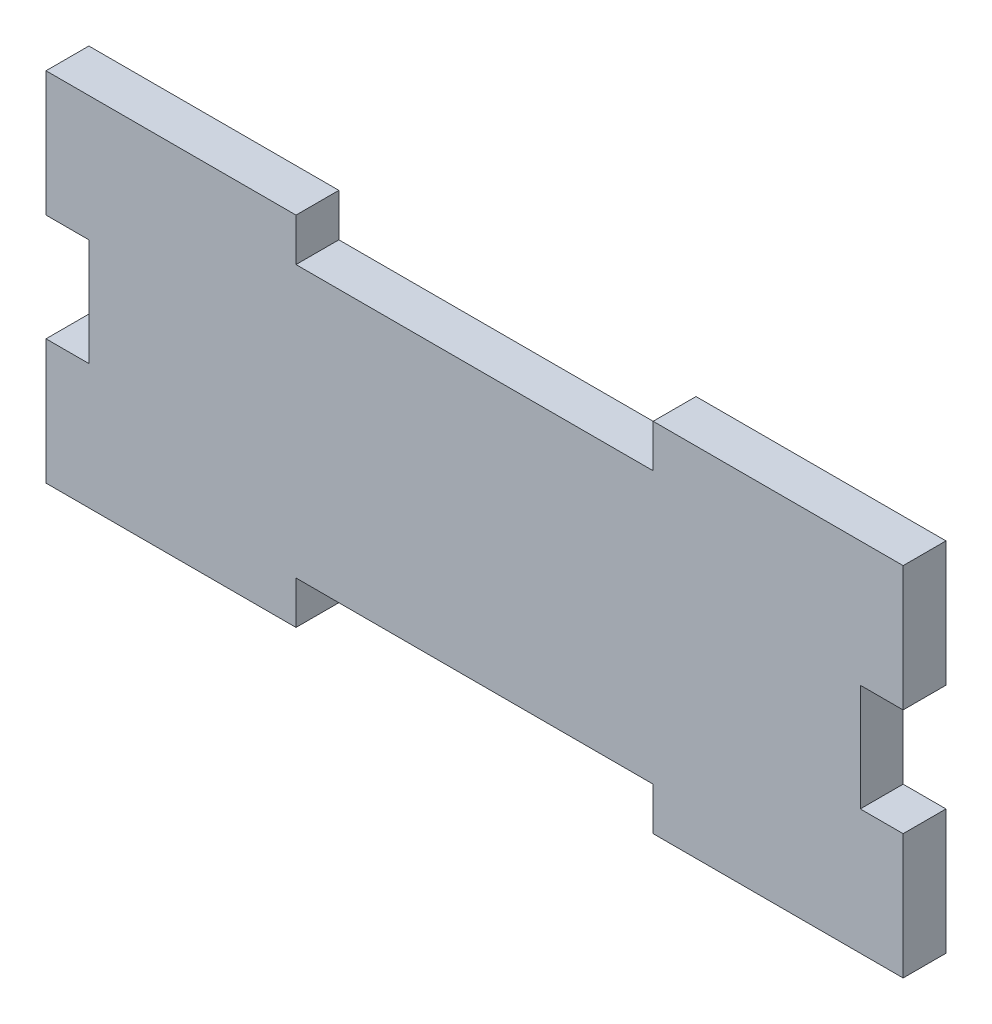
SolidWorks part; units mm, degrees
material "6061-T6 (SS)"
ref_plane "Alzado" through (0, 0, 0) normal (0, 0, 1) x (1, 0, 0)
ref_plane "Planta" through (0, 0, 0) normal (0, 1, 0) x (1, 0, 0)
ref_plane "Vista lateral" through (0, 0, 0) normal (1, 0, 0) x (0, 0, -1)
sketch "Croquis1" plane through (0, 0, 0) normal (0, 0, 1) x (1, 0, 0)
  line L0 (-25, 19) -> (-25, 25)
  line L1 (-25, -19) -> (25, -19)
  line L2 (-60, -25) -> (-60, -7.5)
  line L3 (-25, 19) -> (25, 19)
  line L4 (60, -25) -> (60, -7.5)
  line L5 (25, 25) -> (60, 25)
  line L6 (25, 19) -> (25, 25)
  line L7 (-25, 25) -> (-60, 25)
  line L8 (-54, 0) -> (54, 0) construction
  line L9 (0, -19) -> (0, 19) construction
  line L10 (25, -25) -> (60, -25)
  line L11 (25, -19) -> (25, -25)
  line L12 (-25, -19) -> (-25, -25)
  line L13 (-25, -25) -> (-60, -25)
  line L14 (-60, 7.5) -> (-60, 25)
  line L15 (-60, 7.5) -> (-54, 7.5)
  line L17 (-60, -7.5) -> (-54, -7.5)
  line L18 (-54, 7.5) -> (-54, -7.5)
  line L19 (60, -7.5) -> (54, -7.5)
  line L20 (54, 7.5) -> (54, -7.5)
  line L21 (60, 7.5) -> (54, 7.5)
  line L22 (60, 7.5) -> (60, 25)
  point P0 (0, 0)
  point P1 (-54, 0)
  point P24 (0, 0)
  dimension "D1" = 50
  dimension "D2" = 120
  dimension "D3" = 6
  dimension "D4" = 50
  dimension "D5" = 6
  dimension "D6" = 15
  dimension "D7" = 6
extrude "Saliente-Extruir1" add sketch "Croquis1" along normal blind 6
